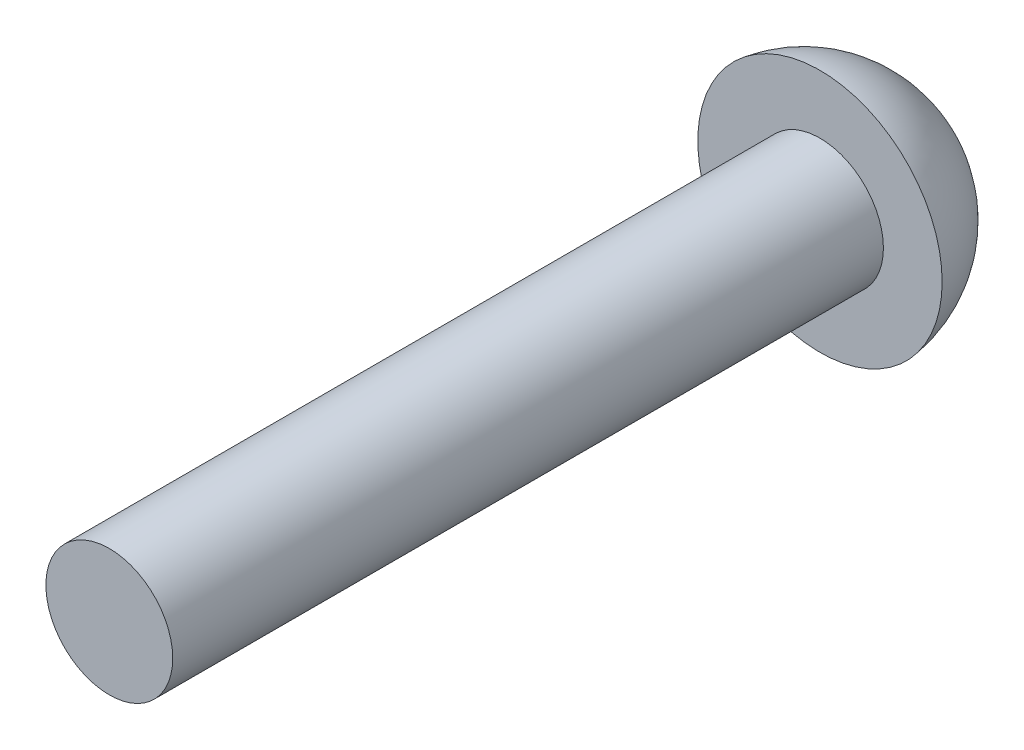
SolidWorks part; units mm, degrees
ref_plane "Front" through (0, 0, 0) normal (0, 0, 1) x (1, 0, 0)
ref_plane "Top" through (0, 0, 0) normal (0, 1, 0) x (1, 0, 0)
ref_plane "Right" through (0, 0, 0) normal (1, 0, 0) x (0, 0, -1)
sketch "Sketch1" plane through (0, 0, 0) normal (0, 1, 0) x (1, 0, 0)
  line L0 (0, 0) -> (0, 21.92)
  line L1 (0, 0) -> (1.7, 0)
  line L2 (1.7, 0) -> (1.7, 19.05)
  line L3 (1.7, 19.05) -> (3.275, 19.05)
  arc A0 (3.275, 19.05) -> (0, 21.92) centre (0, 18.6164) ccw
  dimension "D1" = 3.275
  dimension "D2" = 2.87
  dimension "D3" = 1.7
  dimension "D4" = 19.05
revolve "Revolve1" add sketch "Sketch1" angle 360 about L0
